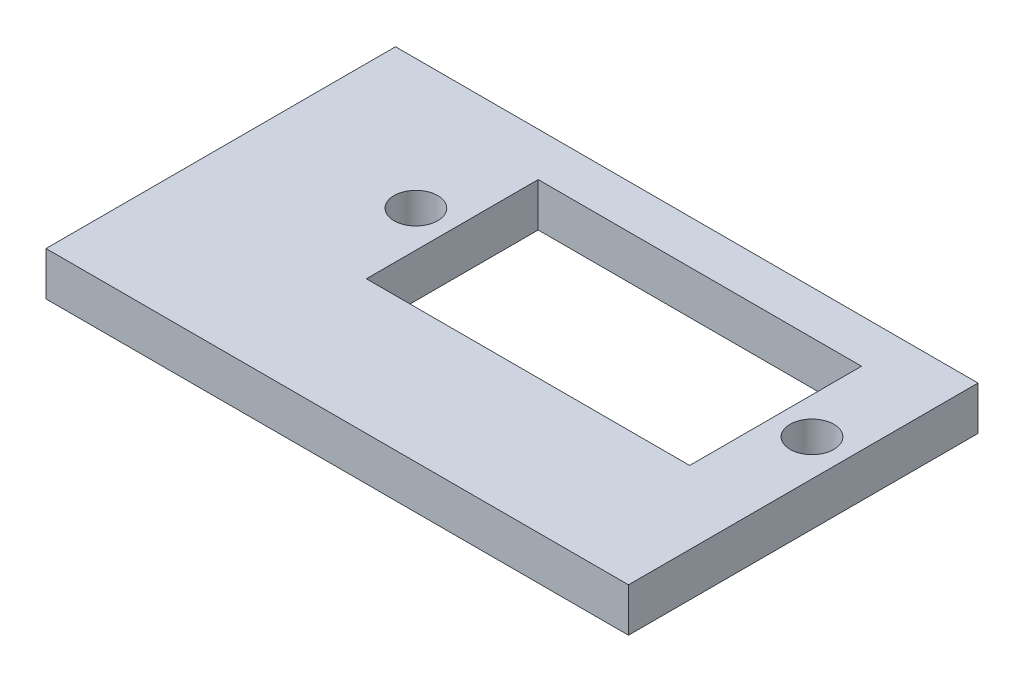
SolidWorks part; units mm, degrees
ref_plane "Front Plane" through (0, 0, 0) normal (0, 0, 1) x (1, 0, 0)
ref_plane "Top Plane" through (0, 0, 0) normal (0, 1, 0) x (1, 0, 0)
ref_plane "Right Plane" through (0, 0, 0) normal (1, 0, 0) x (0, 0, -1)
sketch "Sketch1" plane through (0, 0, 0) normal (0, 1, 0) x (1, 0, 0)
  line L1 (0, 0) -> (40, 0)
  line L2 (0, 0) -> (0, 21)
  line L3 (0, 21) -> (40, 21)
  line L4 (40, 0) -> (40, 21)
  dimension "D1" = 40
  dimension "D2" = 21
extrude "Boss-Extrude1" add sketch "Sketch1" along normal blind 3
sketch "Sketch2" plane through (0, 0, -21) normal (0, 0, -1) x (-1, 0, 0)
  line L1 (0, 3) -> (-40, 3)
  line L2 (0, 3) -> (0, 0)
  line L3 (0, 0) -> (-40, 0)
  line L4 (-40, 3) -> (-40, 0)
extrude "Boss-Extrude2" add sketch "Sketch2" along normal blind 3
sketch "Sketch3" plane through (0, 3, 0) normal (0, 1, 0) x (1, 0, 0)
  line L0 (12.8, 21) -> (35, 21)
  line L3 (40, 0) -> (40, 24) construction
  line L4 (0, 24) -> (40, 24) construction
  line L5 (12.8, 21) -> (12.8, 9.2)
  line L6 (12.8, 9.2) -> (35, 9.2)
  line L7 (35, 21) -> (35, 9.2)
  point P6 (23.9, 21)
  dimension "D1" = 5
  dimension "D2" = 11.8
  dimension "D3" = 22.2
  dimension "D4" = 3
extrude "Cut-Extrude1" cut sketch "Sketch3" against normal blind 10
sketch "Sketch4" plane through (0, 3, 0) normal (0, 1, 0) x (1, 0, 0)
  line L0 (12.8, 21) -> (12.8, 9.2) construction
  line L1 (35, 9.2) -> (35, 21) construction
  circle A0 centre (10.3, 15.1) radius 1.5
  circle A1 centre (37.5, 15.1) radius 1.5
  point P5 (12.8, 15.1)
  dimension "D1" = 3
  dimension "D2" = 2.5
  dimension "D3" = 2.5
extrude "Cut-Extrude2" cut sketch "Sketch4" against normal blind 10
